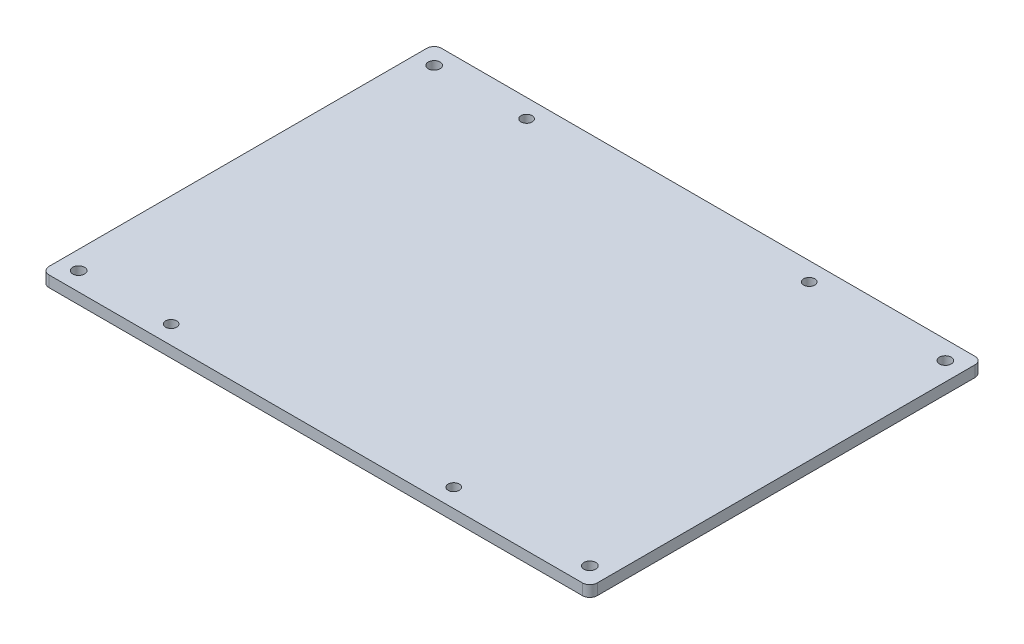
SolidWorks part; units mm, degrees
material "Acrylic (Medium-high impact)"
ref_plane "Front Plane" through (0, 0, 0) normal (0, 0, 1) x (1, 0, 0)
ref_plane "Top Plane" through (0, 0, 0) normal (0, 1, 0) x (1, 0, 0)
ref_plane "Right Plane" through (0, 0, 0) normal (1, 0, 0) x (0, 0, -1)
sketch "Sketch1" plane through (0, 0, 0) normal (0, 1, 0) x (1, 0, 0)
  line L0 (-74.1, 53.05) -> (74.1, 53.05)
  line L1 (-64.1, 43.05) -> (64.1, 43.05) construction
  line L2 (-64.1, 43.05) -> (-64.1, -43.05) construction
  line L3 (-64.1, -43.05) -> (64.1, -43.05) construction
  line L4 (64.1, 43.05) -> (64.1, -43.05) construction
  line L5 (-64.1, 43.05) -> (64.1, -43.05) construction
  line L6 (-64.1, -43.05) -> (64.1, 43.05) construction
  line L7 (74.1, 53.05) -> (74.1, -53.05)
  line L8 (-74.1, -53.05) -> (74.1, -53.05)
  line L9 (-74.1, 53.05) -> (-74.1, -53.05)
  line L10 (-64.1, 43.05) -> (-74.1, 53.05) construction
  line L11 (-74.1, 0) -> (74.1, 0) construction
  line L12 (0, 53.05) -> (0, -53.05) construction
  circle A0 centre (-69.1, 48.05) radius 1.6
  circle A1 centre (-69.1, -48.05) radius 1.6
  circle A2 centre (69.1, -48.05) radius 1.6
  circle A3 centre (69.1, 48.05) radius 1.6
  point P0 (0, 0)
  dimension "D4" = 3.2
  dimension "D1" = 128.2
  dimension "D2" = 86.1
  dimension "D3" = 10
extrude "Boss-Extrude1" add sketch "Sketch1" along normal blind 3
fillet "Fillet1" radius 2 4 edges at (74.1, 1.5, 53.05) (74.1, 1.5, -53.05) (-74.1, 1.5, -53.05) (-74.1, 1.5, 53.05)
sketch "Sketch3" plane through (0, 0, 0) normal (0, -1, 0) x (1, 0, 0)
  line L0 (74.1, 0) -> (0, 0) construction
  line L1 (74.1, 51.05) -> (74.1, -51.05) construction
  circle A0 centre (32.3, 48.05) radius 1.5
  circle A1 centre (32.3, 48.05) radius 1.5 construction
  circle A2 centre (-44.1, 48.05) radius 1.5
  circle A3 centre (-44.1, 48.05) radius 1.5 construction
  circle A4 centre (-44.1, -48.05) radius 1.5
  circle A5 centre (32.3, -48.05) radius 1.5
extrude "Cut-Extrude1" cut sketch "Sketch3" against normal up to next
